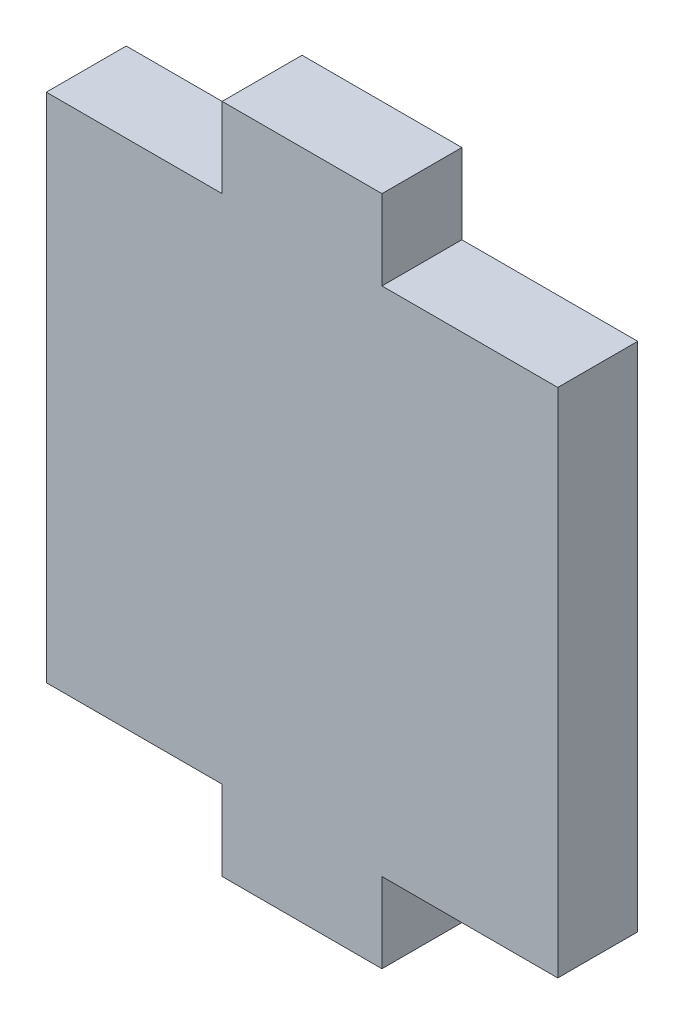
SolidWorks part; units mm, degrees
ref_plane "Front Plane" through (0, 0, 0) normal (0, 0, 1) x (1, 0, 0)
ref_plane "Top Plane" through (0, 0, 0) normal (0, 1, 0) x (1, 0, 0)
ref_plane "Right Plane" through (0, 0, 0) normal (1, 0, 0) x (0, 0, -1)
sketch "Sketch1" plane through (0, 0, 0) normal (0, 0, 1) x (1, 0, 0)
  line L0 (-3.175, -10.9537) -> (-3.175, -14.1288)
  line L5 (10.16, -10.9537) -> (-10.16, 9.3662) construction
  line L6 (10.16, 9.3662) -> (-10.16, -10.9538) construction
  line L7 (-3.175, -14.1288) -> (3.175, -14.1288)
  line L8 (3.175, -14.1288) -> (3.175, -10.9538)
  line L9 (-10.16, -10.9538) -> (-3.175, -10.9537)
  line L10 (3.175, -10.9538) -> (10.16, -10.9537)
  line L11 (-3.175, 9.3662) -> (-10.16, 9.3662)
  line L12 (-3.175, 12.5412) -> (3.175, 12.5412)
  line L13 (-3.175, 12.5412) -> (-3.175, 9.3662)
  line L15 (3.175, 12.5412) -> (3.175, 9.3662)
  line L18 (3.175, 9.3662) -> (10.16, 9.3662)
  line L19 (-10.16, 9.3662) -> (-10.16, -10.9538)
  line L20 (10.16, -10.9537) -> (10.16, 9.3662)
  dimension "D3" = 3.175
  dimension "D4" = 6.35
  dimension "D5" = 3.175
  dimension "D6" = 6.35
  dimension "D7" = 20.32
  dimension "D8" = 6.985
  dimension "D9" = 6.985
extrude "Boss-Extrude1" add sketch "Sketch1" along normal blind 3.175
